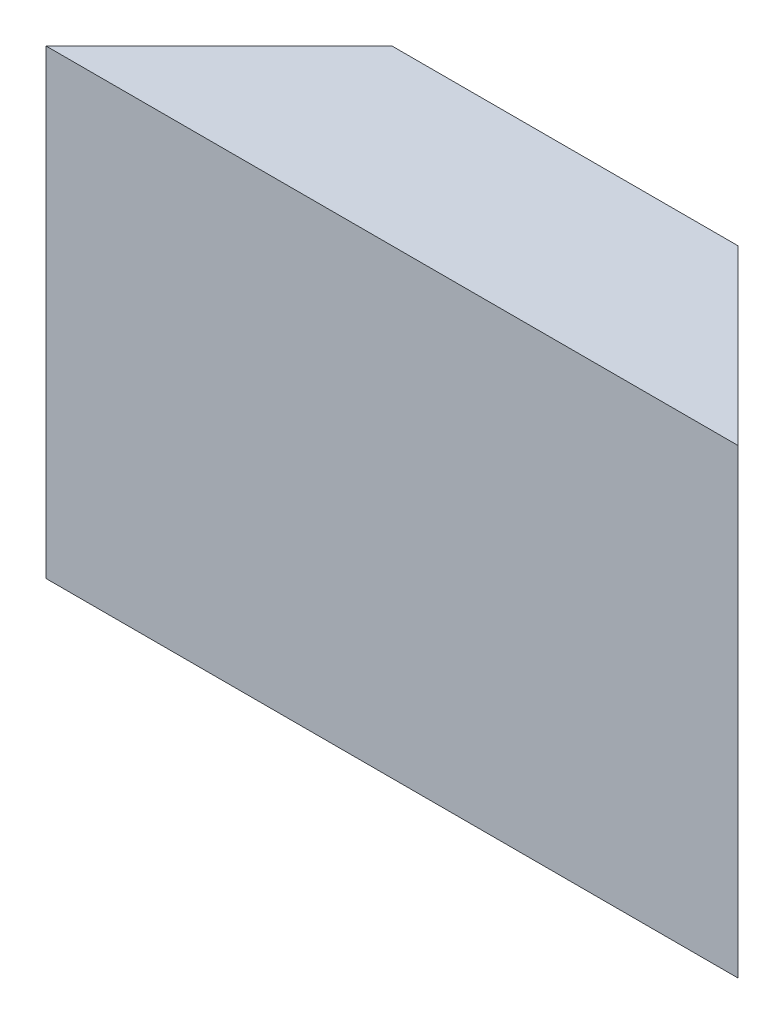
SolidWorks part; units mm, degrees
material "C1"
ref_plane "前基準面" through (0, 0, 0) normal (0, 0, 1) x (1, 0, 0)
ref_plane "上基準面" through (0, 0, 0) normal (0, 1, 0) x (1, 0, 0)
ref_plane "右基準面" through (0, 0, 0) normal (1, 0, 0) x (0, 0, -1)
sketch "草圖1" plane through (0, 0, 0) normal (0, 1, 0) x (1, 0, 0)
  line L0 (0, 0) -> (60, 0)
  line L1 (60, 0) -> (45, 15)
  line L2 (45, 15) -> (15, 15)
  line L3 (15, 15) -> (0, 0)
  dimension "D1" = 60
  dimension "D2" = 15
extrude "填料-伸長1" add sketch "草圖1" along normal blind 40
